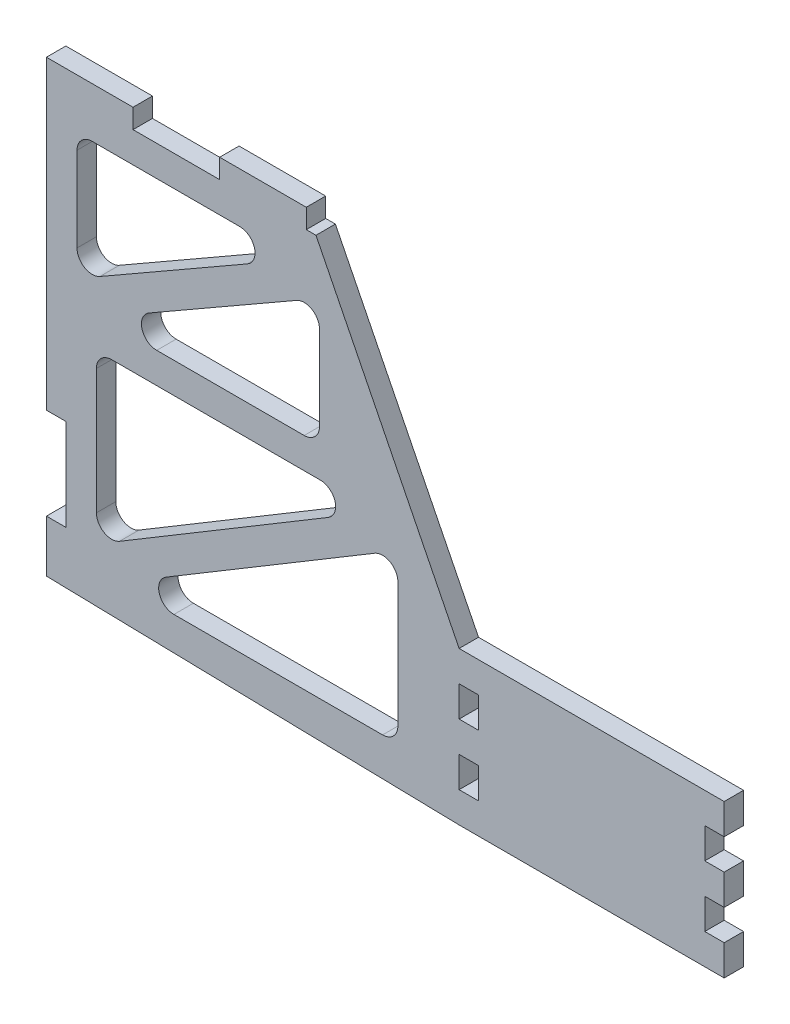
SolidWorks part; units mm, degrees
ref_plane "Front Plane" through (0, 0, 0) normal (0, 0, 1) x (1, 0, 0)
ref_plane "Top Plane" through (0, 0, 0) normal (0, 1, 0) x (1, 0, 0)
ref_plane "Right Plane" through (0, 0, 0) normal (1, 0, 0) x (0, 0, -1)
sketch "Sketch1" plane through (0, 0, 0) normal (0, 0, 1) x (1, 0, 0)
  line L0 (86.7, -50) -> (86.7, 0)
  line L1 (86.7, 0) -> (0, 0)
  line L2 (0, 0) -> (-50, 100)
  line L3 (-50, 100) -> (-135, 100)
  line L4 (-135, 100) -> (-135, -47)
  line L5 (-135, -47) -> (0, -50)
  line L6 (0, -50) -> (86.7, -50)
  point P10 (0, 0)
  point P19 (86.7, 0)
  dimension "D5" = 50
  dimension "D6" = 47
  dimension "D1" = 86.7
  dimension "D2" = 50
  dimension "D3" = 85
  dimension "D4" = 150
extrude "Body" add sketch "Sketch1" along normal blind 6.35
sketch "Sketch2" plane through (0, 0, 6.35) normal (0, 0, 1) x (1, 0, 0)
  line L0 (-135, 100) -> (-135, -47) construction
  line L1 (-135, -30) -> (-128.65, -30)
  line L2 (-135, -30) -> (-135, 0)
  line L3 (-135, 0) -> (-128.65, 0)
  line L4 (-128.65, -30) -> (-128.65, 0)
  line L5 (86.7, 0) -> (0, 0) construction
  dimension "D1" = 6.35
  dimension "D2" = 30
extrude "Cross support" cut sketch "Sketch2" against normal up to next
sketch "Sketch3" plane through (0, 0, 6.35) normal (0, 0, 1) x (1, 0, 0)
  line L0 (86.7, -10) -> (80.35, -10)
  line L1 (86.7, -50) -> (86.7, 0) construction
  line L2 (80.35, -10) -> (80.35, -20)
  line L3 (80.35, -20) -> (86.7, -20)
  line L4 (86.7, -10) -> (86.7, -20)
  line L5 (86.7, -30) -> (80.35, -30)
  line L6 (80.35, -30) -> (80.35, -40)
  line L7 (80.35, -40) -> (86.7, -40)
  line L8 (86.7, -30) -> (86.7, -40)
  line L9 (80.35, 0) -> (80.35, -10) construction
  line L10 (86.7, 0) -> (0, 0) construction
  line L11 (80.35, -20) -> (80.35, -30) construction
  line L12 (80.35, -40) -> (80.35, -50) construction
  line L13 (0, -50) -> (86.7, -50) construction
  line L14 (0, 0) -> (0, -50) construction
  line L15 (0, -30) -> (6.35, -30)
  line L16 (0, -20) -> (0, -10)
  line L17 (0, -10) -> (6.35, -10)
  line L18 (6.35, -20) -> (6.35, -10)
  line L19 (6.35, -20) -> (0, -20)
  line L20 (6.35, -30) -> (6.35, -40)
  line L21 (6.35, -40) -> (0, -40)
  line L22 (0, -40) -> (0, -30)
  line L23 (86.7, 0) -> (0, 0) construction
  line L24 (6.35, -10) -> (6.35, 0) construction
  line L25 (6.35, -20) -> (6.35, -30) construction
  line L26 (6.35, -40) -> (6.35, -50) construction
  dimension "D1" = 6.35
  dimension "D2" = 6.35
extrude "Side supports" cut sketch "Sketch3" against normal up to next
sketch "Sketch4" plane through (0, 0, 6.35) normal (0, 0, 1) x (1, 0, 0)
  line L0 (-106.6667, 100) -> (-106.6667, 93.65)
  line L2 (-50, 100) -> (-135, 100) construction
  line L4 (-106.6667, 93.65) -> (-78.3333, 93.65)
  line L5 (-78.3333, 93.65) -> (-78.3333, 100)
  line L6 (-78.3333, 100) -> (-106.6667, 100)
  line L7 (-46.825, 93.65) -> (-50, 93.65)
  line L8 (0, 0) -> (-50, 100) construction
  line L9 (-50, 93.65) -> (-50, 100)
  line L10 (-50, 100) -> (-46.825, 93.65)
  line L11 (-135, 93.65) -> (-106.6667, 93.65) construction
  line L12 (-135, 100) -> (-135, 0) construction
  line L13 (-78.3333, 93.65) -> (-50, 93.65) construction
  dimension "D1" = 6.35
extrude "Top mounting teeth" cut sketch "Sketch4" against normal up to next
sketch "Sketch5" plane through (0, 0, 6.35) normal (0, 0, 1) x (1, 0, 0)
  line L0 (-106.6667, 93.65) -> (-78.3333, 93.65) construction
  circle A0 centre (-92.5, -1.35) radius 10
  dimension "D1" = 20
  dimension "D2" = 95
extrude "Cable routing hole" [suppressed] cut sketch "Sketch5" against normal up to next
sketch "Sketch6" plane through (0, 0, 6.35) normal (0, 0, 1) x (1, 0, 0)
  line L0 (-118.65, 20) -> (-118.65, -20.8861)
  line L1 (-111.0804, -25.1754) -> (-42.8313, 15.7108)
  line L2 (-45.4009, 25) -> (-113.65, 25)
  line L3 (-93.2845, -37) -> (-25.0354, -37)
  line L4 (-20.0354, -32) -> (-20.0354, 8.8861)
  line L5 (-27.6049, 13.1754) -> (-95.854, -27.7108)
  line L6 (-125, 50.9606) -> (-125, 78.65)
  line L7 (-120, 83.65) -> (-71.7601, 83.65)
  line L8 (-69.271, 74.3136) -> (-117.5109, 46.6242)
  line L9 (-101.4088, 44.3364) -> (-53.1689, 72.0258)
  line L10 (-45.6799, 67.6894) -> (-45.6799, 40)
  line L11 (-50.6799, 35) -> (-98.9197, 35)
  line L12 (-135, 100) -> (-135, 0) construction
  line L13 (-106.6667, 93.65) -> (-78.3333, 93.65) construction
  line L14 (-128.65, -30) -> (-128.65, 0) construction
  line L15 (0, 0) -> (-46.825, 93.65) construction
  line L16 (-111.3601, -37) -> (-118.65, -37) construction
  line L17 (-118.65, -37) -> (-118.65, -29.7101) construction
  line L18 (-27.3253, 25) -> (-20.0354, 25) construction
  line L19 (-20.0354, 25) -> (-20.0354, 17.7101) construction
  line L20 (-53.0053, 83.65) -> (-45.6799, 83.65) construction
  line L21 (-45.6799, 83.65) -> (-45.6799, 76.3245) construction
  line L22 (-117.6745, 35) -> (-125, 35) construction
  line L23 (-125, 35) -> (-125, 42.3255) construction
  arc A0 (-53.1689, 72.0258) -> (-45.6799, 67.6894) centre (-50.6799, 67.6894) cw
  arc A1 (-50.6799, 35) -> (-45.6799, 40) centre (-50.6799, 40) ccw
  arc A2 (-98.9197, 35) -> (-101.4088, 44.3364) centre (-98.9197, 40) cw
  arc A3 (-125, 50.9606) -> (-117.5109, 46.6242) centre (-120, 50.9606) ccw
  arc A4 (-120, 83.65) -> (-125, 78.65) centre (-120, 78.65) ccw
  arc A5 (-69.271, 74.3136) -> (-71.7601, 83.65) centre (-71.7601, 78.65) ccw
  arc A6 (-45.4009, 25) -> (-42.8313, 15.7108) centre (-45.4009, 20) cw
  arc A7 (-118.65, 20) -> (-113.65, 25) centre (-113.65, 20) cw
  arc A8 (-118.65, -20.8861) -> (-111.0804, -25.1754) centre (-113.65, -20.8861) ccw
  arc A9 (-93.2845, -37) -> (-95.854, -27.7108) centre (-93.2845, -32) cw
  arc A10 (-25.0354, -37) -> (-20.0354, -32) centre (-25.0354, -32) ccw
  arc A11 (-27.6049, 13.1754) -> (-20.0354, 8.8861) centre (-25.0354, 8.8861) cw
  dimension "D10" = 5
  dimension "D11" = 5
  dimension "D12" = 5
  dimension "D13" = 5
  dimension "D14" = 5
  dimension "D15" = 5
  dimension "D16" = 5
  dimension "D17" = 5
  dimension "D18" = 5
  dimension "D19" = 5
  dimension "D20" = 5
  dimension "D21" = 5
  dimension "D1" = 10
  dimension "D2" = 10
  dimension "D3" = 10
  dimension "D4" = 10
  dimension "D5" = 10
  dimension "D6" = 10
  dimension "D7" = 10
  dimension "D8" = 10
  dimension "D9" = 10
  dimension "D22" = 75
extrude "Lightning holes" cut sketch "Sketch6" against normal up to next
